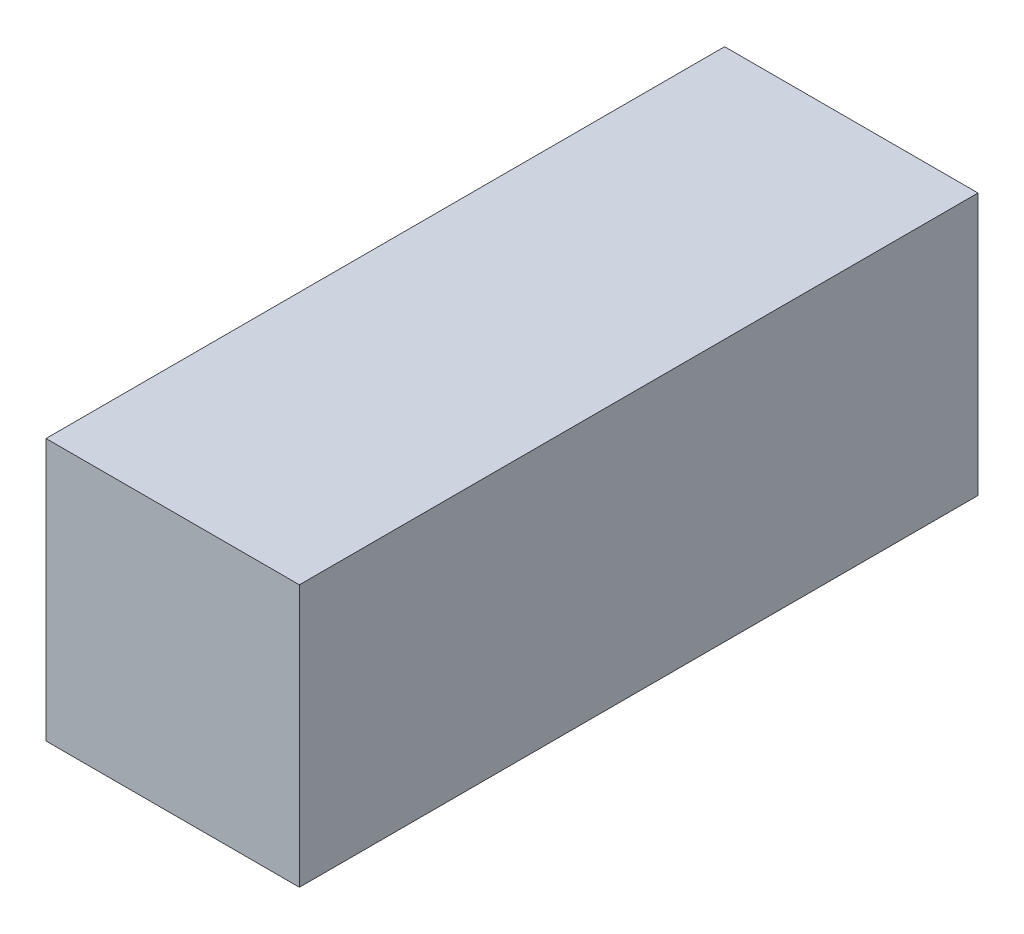
SolidWorks part; units mm, degrees
ref_plane "Front Plane" through (0, 0, 0) normal (0, 0, 1) x (1, 0, 0)
ref_plane "Top Plane" through (0, 0, 0) normal (0, 1, 0) x (1, 0, 0)
ref_plane "Right Plane" through (0, 0, 0) normal (1, 0, 0) x (0, 0, -1)
sketch "Sketch2" plane through (0, 0, 0) normal (0, 1, 0) x (1, 0, 0)
  line L0 (29.5, 0) -> (-29.5, 0) construction
  line L1 (-29.5, -79) -> (29.5, -79)
  line L2 (-29.5, -79) -> (-29.5, 79)
  line L3 (-29.5, 79) -> (29.5, 79)
  line L4 (29.5, -79) -> (29.5, 79)
  point P4 (29.5, 0)
  point P8 (0, 79)
  dimension "D1" = 158
  dimension "D2" = 59
extrude "11000mah battery" add sketch "Sketch2" along normal blind 61
sketch "Sketch3" plane through (0, 61, 0) normal (0, 1, 0) x (1, 0, 0)
  line L0 (-29.5, 0) -> (29.5, 0) construction
  line L1 (-29.5, 79) -> (-29.5, -79) construction
  line L2 (29.5, -79) -> (29.5, 79) construction
